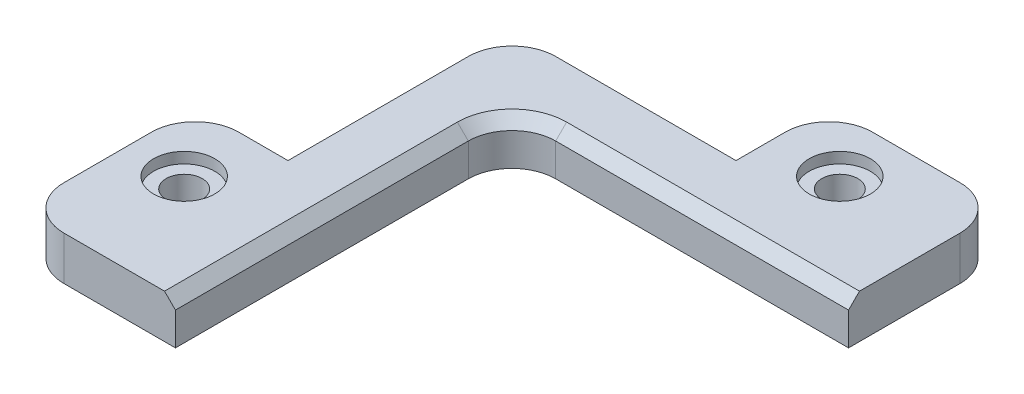
SolidWorks part; units mm, degrees
ref_plane "Alzado" through (0, 0, 0) normal (0, 0, 1) x (1, 0, 0)
ref_plane "Planta" through (0, 0, 0) normal (0, 1, 0) x (1, 0, 0)
ref_plane "Vista lateral" through (0, 0, 0) normal (1, 0, 0) x (0, 0, -1)
sketch "Croquis1" plane through (0, 0, 0) normal (0, 1, 0) x (1, 0, 0)
  line L0 (0, 0) -> (0, 45)
  line L1 (0, 45) -> (45, 45)
  line L2 (45, 45) -> (45, 35)
  line L3 (45, 35) -> (10, 35)
  line L4 (10, 35) -> (10, 0)
  line L5 (10, 0) -> (0, 0)
  line L6 (5, 0) -> (5, 45) construction
  line L7 (45, 40) -> (0, 40) construction
  circle A0 centre (35, 40) radius 1.65
  circle A1 centre (5, 10) radius 1.65
  dimension "D3" = 3.3
  dimension "D4" = 3.3
  dimension "D1" = 10
  dimension "D2" = 10
  dimension "D5" = 30
  dimension "D6" = 30
  dimension "D7" = 45
  dimension "D8" = 45
extrude "Saliente-Extruir1" add sketch "Croquis1" along normal blind 4
sketch "Croquis2" plane through (0, 4, 0) normal (0, 1, 0) x (1, 0, 0)
  line L0 (10, 35) -> (45, 35) construction
  line L1 (10, 0) -> (14.2, 0)
  line L2 (10, 0) -> (10, 35)
  line L3 (10, 35) -> (14.2, 35)
  line L4 (14.2, 0) -> (14.2, 35)
  line L6 (45, 35) -> (14.2, 35)
  line L7 (45, 35) -> (45, 30.8)
  line L8 (45, 30.8) -> (14.2, 30.8)
  line L9 (14.2, 35) -> (14.2, 30.8)
  line M6 (10, 0) -> (10, 35)
  line M7 (10, 35) -> (45, 35)
  dimension "D1" = 4.2
  dimension "D2" = 4.2
extrude "Saliente-Extruir2" add sketch "Croquis2" against normal up to surface (4 mm away) contours L8 L7 L4 M7 | L1 L4 M7 M6 up to face at (35, 0, -38.35)
sketch "Croquis3" plane through (0, 4, 0) normal (0, 1, 0) x (1, 0, 0)
  line L1 (0, 45) -> (29, 45)
  line L2 (0, 45) -> (0, 36.5)
  line L3 (0, 36.5) -> (29, 36.5)
  line L4 (29, 45) -> (29, 36.5)
  line L5 (0, 36.5) -> (8.5, 36.5)
  line L6 (0, 36.5) -> (0, 16)
  line L7 (0, 16) -> (8.5, 16)
  line L8 (8.5, 36.5) -> (8.5, 16)
  line M9 (45, 45) -> (0, 45)
  line M10 (0, 45) -> (0, 0)
  dimension "D1" = 8.5
  dimension "D2" = 29
  dimension "D3" = 8.5
  dimension "D4" = 20.5
extrude "Cortar-Extruir1" cut sketch "Croquis3" against normal up to surface (4 mm away) contours L4 L3 M9 M10 | L8 L3 L7 M10 up to face at (35, 0, -38.35)
fillet "Redondeo1" radius 4 2 edges at (14.2, 2, -30.8) (8.5, 2, -36.5)
fillet "Redondeo2" radius 4 4 edges at (0, 2, 0) (0, 2, -16) (29, 2, -45) (45, 2, -45)
chamfer "Chaflán1" distance 1 angle 45 3 edges at (14.2, 4, -13.4) (15.3716, 4, -29.6284) (31.6, 4, -30.8)
sketch "Croquis4" plane through (0, 4, 0) normal (0, 1, 0) x (1, 0, 0)
  circle A0 centre (35, 40) radius 2.8
  circle A1 centre (5, 10) radius 2.8
  dimension "D1" = 5.6
  dimension "D2" = 5.6
extrude "Cortar-Extruir2" cut sketch "Croquis4" against normal blind 1
